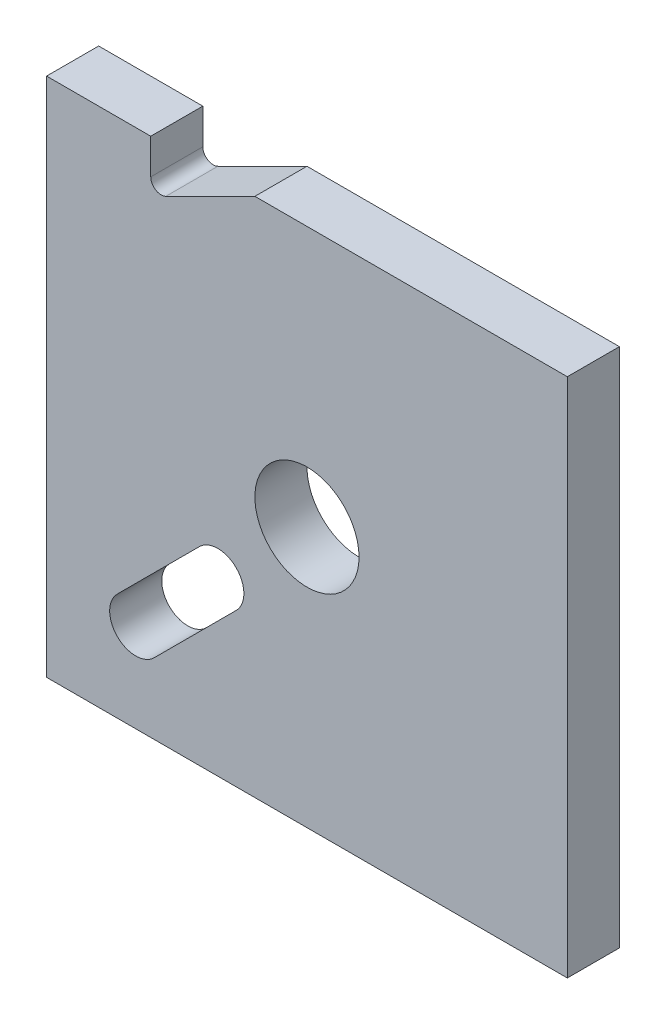
SolidWorks part; units mm, degrees
ref_plane "Front Plane" through (0, 0, 0) normal (0, 0, 1) x (1, 0, 0)
ref_plane "Top Plane" through (0, 0, 0) normal (0, 1, 0) x (1, 0, 0)
ref_plane "Right Plane" through (0, 0, 0) normal (1, 0, 0) x (0, 0, -1)
sketch "Sketch1" plane through (0, 0, 0) normal (0, 0, 1) x (1, 0, 0)
  line L1 (-25, 25) -> (25, 25)
  line L2 (-25, 25) -> (-25, -25)
  line L3 (-25, -25) -> (25, -25)
  line L4 (25, 25) -> (25, -25)
  line L5 (-25, 25) -> (25, -25) construction
  line L6 (-25, -25) -> (25, 25) construction
  circle A0 centre (0, 0) radius 5
  point P0 (0, 0)
  dimension "D2" = 10
  dimension "D1" = 50
extrude "Boss-Extrude1" add sketch "Sketch1" along normal mid plane 5
sketch "Sketch4" plane through (0, 0, 2.5) normal (0, 0, 1) x (1, 0, 0)
  line L0 (-15, 25) -> (-15, 20)
  line L1 (-15, 20) -> (-5, 25)
  line L4 (25, -25) -> (25, 25)
  line L5 (25, 25) -> (-25, 25)
  line L6 (-25, 25) -> (-25, -25)
  line L7 (-25, -25) -> (25, -25)
  line L8 (25, -25) -> (25, 25)
  line L9 (25, 25) -> (-25, 25)
  line L10 (-25, 25) -> (-25, -25)
  line L11 (-25, -25) -> (25, -25)
  point P9 (0, 0)
  line M6 (25, 25) -> (-25, 25)
  dimension "D2" = 10
  dimension "D3" = 5
  dimension "D4" = 10
  dimension "D1" = 0
extrude "Cut-Extrude2" cut sketch "Sketch4" against normal blind 5 and the other way through all contours L0 L1 M6
fillet "Fillet1" radius 1 1 edges at (-15, 20, 0)
sketch "Sketch5" plane through (0, 0, 2.5) normal (0, 0, 1) x (1, 0, 0)
  line L0 (-25, -25) -> (0, 0) construction
  line L1 (-8.5581, -8.5581) -> (-16.4419, -16.4419) construction
  line L2 (-6.7903, -10.3258) -> (-14.6742, -18.2097)
  line L3 (-10.3258, -6.7903) -> (-18.2097, -14.6742)
  arc A0 (-6.7903, -10.3258) -> (-10.3258, -6.7903) centre (-8.5581, -8.5581) ccw
  arc A1 (-18.2097, -14.6742) -> (-14.6742, -18.2097) centre (-16.4419, -16.4419) ccw
  point P6 (-12.5, -12.5)
  dimension "D1" = 2.5
  dimension "D2" = 7.8839
extrude "Cut-Extrude3" cut sketch "Sketch5" against normal through all
